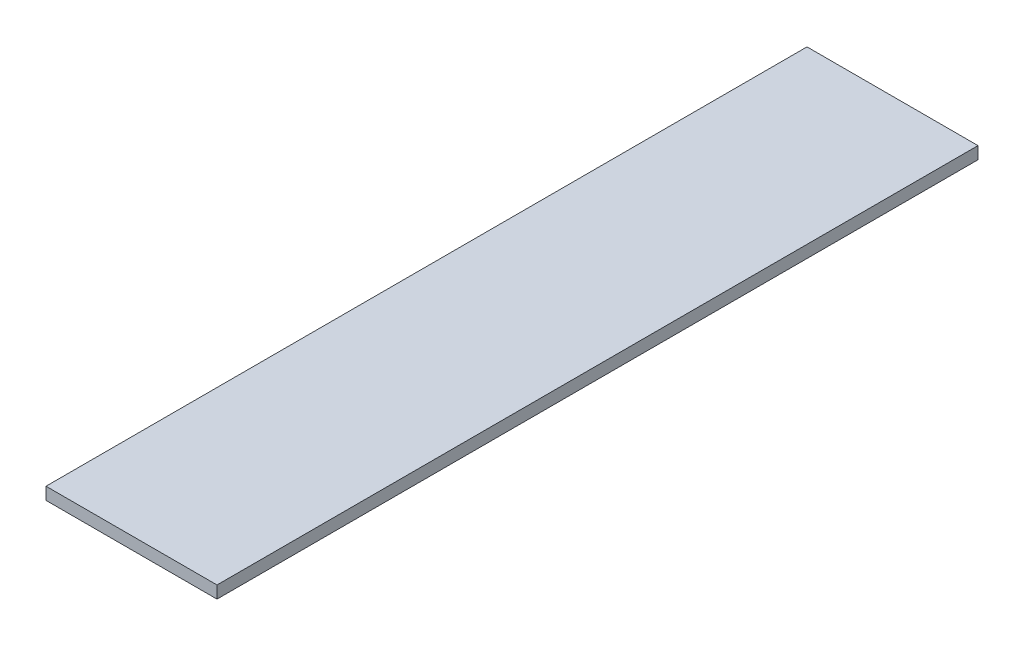
SolidWorks part; units mm, degrees
material "Pine"
ref_plane "Front Plane" through (0, 0, 0) normal (0, 0, 1) x (1, 0, 0)
ref_plane "Top Plane" through (0, 0, 0) normal (0, 1, 0) x (1, 0, 0)
ref_plane "Right Plane" through (0, 0, 0) normal (1, 0, 0) x (0, 0, -1)
sketch "Sketch1" plane through (0, 0, 0) normal (0, 1, 0) x (1, 0, 0)
  line L1 (-127, 0) -> (127, 0)
  line L2 (-127, 0) -> (-127, -1130.3)
  line L3 (-127, -1130.3) -> (127, -1130.3)
  line L4 (127, 0) -> (127, -1130.3)
  point P5 (0, 0)
  dimension "D1" = 254
  dimension "D2" = 1130.3
extrude "Boss-Extrude1" add sketch "Sketch1" along normal blind 18.2562
sketch "Sketch2" plane through (0, 18.2562, 0) normal (0, 1, 0) x (1, 0, 0)
  line L0 (-127, -1130.3) -> (127, -1130.3) construction
  line L1 (-101.6, -723.9) -> (101.6, -723.9)
  line L2 (-101.6, -723.9) -> (-101.6, -1098.55)
  line L3 (-101.6, -1098.55) -> (101.6, -1098.55)
  line L4 (101.6, -723.9) -> (101.6, -1098.55)
  point P4 (0, -723.9)
  dimension "D1" = 101.6
  dimension "D2" = 31.75
  dimension "D3" = 374.65
sketch "Sketch6" plane through (0, 18.2562, 0) normal (0, 1, 0) x (1, 0, 0)
  line L0 (127, -1130.3) -> (127, 0) construction
  line L1 (-101.6, -101.6) -> (101.6, -101.6)
  line L2 (-101.6, -101.6) -> (-101.6, -669.925)
  line L3 (-101.6, -669.925) -> (101.6, -669.925)
  line L4 (101.6, -101.6) -> (101.6, -669.925)
  line L5 (127, 0) -> (-127, 0) construction
  point P4 (-101.6, -385.7625)
  point P5 (101.6, -385.7625)
  point P8 (0, -101.6)
  dimension "D1" = 25.4
  dimension "4" = 101.6
  dimension "D3" = 284.1625
sketch "Sketch7" plane through (0, 18.2562, 0) normal (0, 1, 0) x (1, 0, 0)
  line L0 (0, -49.2125) -> (0, -557.2125)
  line L1 (127, 0) -> (-127, 0) construction
  dimension "D1" = 508
  dimension "D2" = 49.2125
sketch "Sketch5" plane through (0, 18.2562, 0) normal (0, 1, 0) x (1, 0, 0)
  line L0 (127, -1130.3) -> (127, 0) construction
  line L1 (-127, -1130.3) -> (127, -1130.3)
  line L2 (-127, -1130.3) -> (-127, -1128.7125)
  line L3 (-127, -1128.7125) -> (127, -1128.7125)
  line L4 (127, -1130.3) -> (127, -1128.7125)
  dimension "D1" = 1.5875
